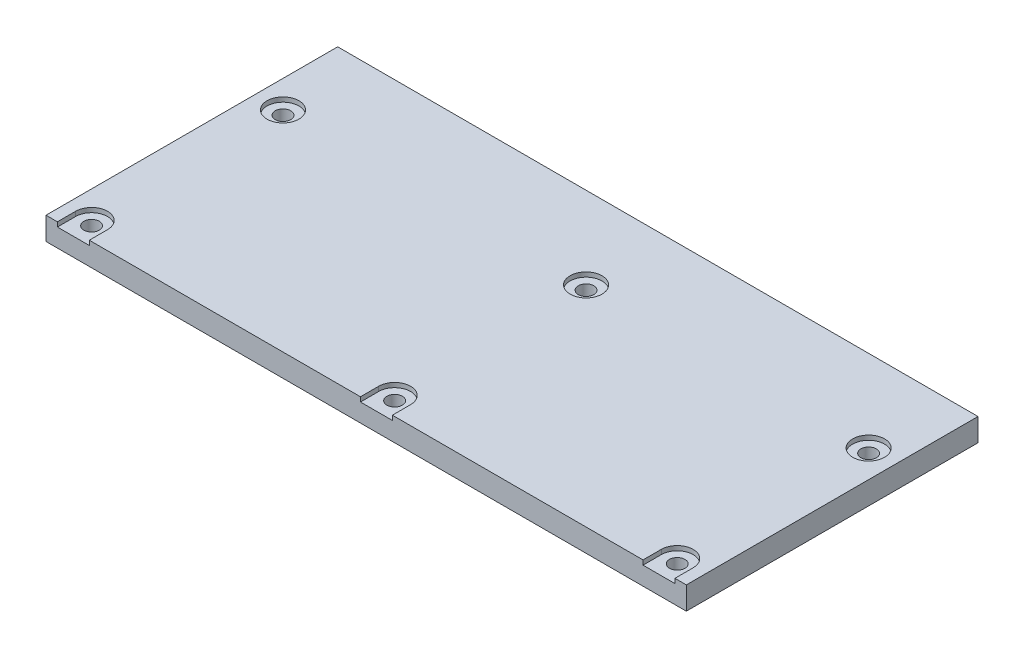
SolidWorks part; units mm, degrees
ref_plane "前视基准面" through (0, 0, 0) normal (0, 0, 1) x (1, 0, 0)
ref_plane "上视基准面" through (0, 0, 0) normal (0, 1, 0) x (1, 0, 0)
ref_plane "右视基准面" through (0, 0, 0) normal (1, 0, 0) x (0, 0, -1)
other "Configuration Table"
sketch "草图1" plane through (0, 0, 0) normal (0, 1, 0) x (1, 0, 0)
  line L0 (-14.7486, 25.8729) -> (-14.7486, -16.1271) construction
  line L1 (-81.2486, 25.8729) -> (47.2514, 25.8729) construction
  line L2 (-81.2486, 25.8729) -> (-81.2486, -16.1271) construction
  line L3 (-81.2486, -16.1271) -> (47.2514, -16.1271) construction
  line L4 (47.2514, 25.8729) -> (47.2514, -16.1271) construction
  line L6 (-87.2486, 43.8729) -> (53.2514, 43.8729)
  line L7 (-87.2486, 43.8729) -> (-87.2486, -20.1271)
  line L8 (-87.2486, -20.1271) -> (53.2514, -20.1271)
  line L9 (53.2514, 43.8729) -> (53.2514, -20.1271)
  point P5 (-14.7486, 25.8729)
  point P6 (-14.7486, -16.1271)
  dimension "D1" = 42
  dimension "D2" = 66.5
  dimension "D3" = 62
  dimension "D4" = 4
  dimension "D5" = 18
  dimension "D6" = 6
  dimension "D7" = 6
  dimension "D8" = 64
  dimension "D9" = 140.5
extrude "凸台-拉伸1" add sketch "草图1" along normal blind 5
sketch "草图2" plane through (0, 5, 0) normal (0, 1, 0) x (1, 0, 0)
  line L0 (-81.2486, -16.1271) -> (-14.7486, -16.1271) construction
  line L1 (-14.7486, -16.1271) -> (-14.7486, 25.8729) construction
  line L2 (-14.7486, 25.8729) -> (47.2514, 25.8729) construction
  line L3 (47.2514, 25.8729) -> (47.2514, -16.1271) construction
  line L4 (47.2514, -16.1271) -> (-14.7486, -16.1271) construction
  line L5 (-81.2486, -16.1271) -> (-81.2486, 25.8729) construction
  line L6 (-81.2486, 25.8729) -> (-14.7486, 25.8729) construction
  line L7 (-87.2486, -20.1271) -> (53.2514, -20.1271) construction
  line L8 (53.2514, -20.1271) -> (53.2514, 43.8729) construction
  line L9 (-87.2486, 43.8729) -> (-87.2486, -20.1271) construction
  line L10 (53.2514, 43.8729) -> (-87.2486, 43.8729) construction
  point P0 (-81.2486, 25.8729)
  point P1 (-81.2486, -16.1271)
  point P2 (-14.7486, 25.8729)
  point P3 (-14.7486, -16.1271)
  point P4 (47.2514, 25.8729)
  point P5 (47.2514, -16.1271)
  dimension "D1" = 62
  dimension "D2" = 66.5
  dimension "D3" = 42
  dimension "D4" = 42
  dimension "D5" = 42
  dimension "D6" = 4
  dimension "D7" = 6
  dimension "D8" = 6
  dimension "D9" = 18
hole_wizard "M3 六角头机械螺钉的柱形沉头孔1" positions "草图2" profile "草图3" counterbore size "M3" standard "ANSI Metric" end condition through all
sketch "草图3" plane through (-81.2486, 5, -25.8729) normal (1, 0, 0) x (0, 0, 1)
  line L0 (0, 0) -> (0, 5)
  line L1 (0, 5) -> (1.7, 5)
  line L3 (1.7, 5) -> (1.7, 1)
  line L4 (1.7, 1) -> (3.5, 1)
  line L5 (3.5, 1) -> (3.5, 0)
  line L7 (3.5, 0) -> (0, 0)
  line L11 (0, -6.35) -> (0, 107.95) construction
  dimension "通孔孔直径" = 3.4
  dimension "通孔孔深度" = 5
  dimension "柱形沉头孔直径" = 7
  dimension "柱形沉头孔深度" = 1
sketch "草图4" plane through (0, 5, 0) normal (0, 1, 0) x (1, 0, 0)
  line L0 (-87.2486, -20.1271) -> (53.2514, -20.1271) construction
  line L1 (-84.7486, -16.1271) -> (-77.7486, -16.1271)
  line L2 (-84.7486, -16.1271) -> (-84.7486, -20.1271)
  line L3 (-84.7486, -20.1271) -> (-77.7486, -20.1271)
  line L4 (-77.7486, -16.1271) -> (-77.7486, -20.1271)
  line L6 (-18.2486, -16.1271) -> (-11.2486, -16.1271)
  line L7 (-18.2486, -16.1271) -> (-18.2486, -20.1271)
  line L8 (-18.2486, -20.1271) -> (-11.2486, -20.1271)
  line L9 (-11.2486, -16.1271) -> (-11.2486, -20.1271)
  line L10 (43.7514, -16.1271) -> (50.7514, -16.1271)
  line L11 (43.7514, -16.1271) -> (43.7514, -20.1271)
  line L12 (43.7514, -20.1271) -> (50.7514, -20.1271)
  line L13 (50.7514, -16.1271) -> (50.7514, -20.1271)
  circle A0 centre (47.2514, -16.1271) radius 1.7 construction
  circle A1 centre (-14.7486, -16.1271) radius 1.7 construction
  circle A2 centre (-81.2486, -16.1271) radius 1.7 construction
  circle A3 centre (47.2514, -16.1271) radius 1.7 construction
  circle A4 centre (-14.7486, -16.1271) radius 1.7 construction
  circle A5 centre (-81.2486, -16.1271) radius 1.7 construction
  circle A6 centre (-81.2486, -16.1271) radius 3.5 construction
  circle A7 centre (-81.2486, -16.1271) radius 3.5 construction
  circle A8 centre (-14.7486, -16.1271) radius 3.5 construction
  circle A9 centre (-14.7486, -16.1271) radius 3.5 construction
  circle A10 centre (47.2514, -16.1271) radius 3.5 construction
  circle A11 centre (47.2514, -16.1271) radius 3.5 construction
  dimension "D1" = 7
  dimension "D2" = 4
  dimension "D3" = 7
  dimension "D4" = 4
  dimension "D5" = 7
  dimension "D6" = 4
extrude "切除-拉伸1" cut sketch "草图4" against normal up to surface (1 mm away) up to face at (-81.2486, 4, 17.8271)
sketch "草图5" plane through (0, 0, 0) normal (0, -1, 0) x (1, 0, 0)
  line L0 (-14.7486, 16.1271) -> (-14.7486, -27.5729) construction
  circle A0 centre (-14.7486, -25.8729) radius 1.7 construction
